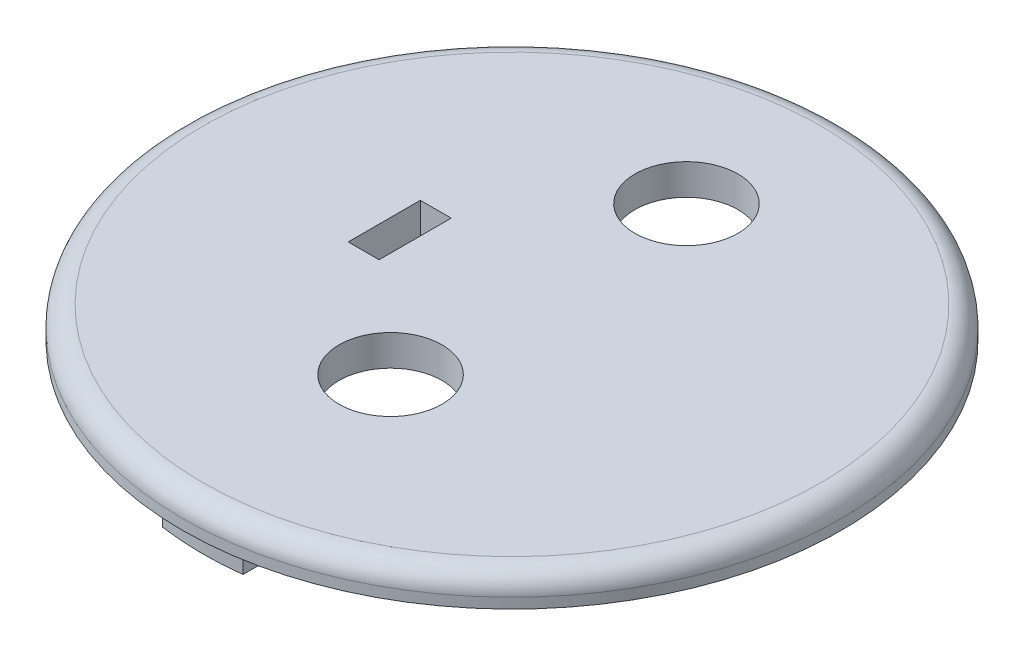
SolidWorks part; units mm, degrees
ref_plane "Plan de face" through (0, 0, 0) normal (0, 0, 1) x (1, 0, 0)
ref_plane "Plan de dessus" through (0, 0, 0) normal (0, 1, 0) x (1, 0, 0)
ref_plane "Plan de droite" through (0, 0, 0) normal (1, 0, 0) x (0, 0, -1)
sketch "Esquisse2" plane through (0, 0, 0) normal (0, 1, 0) x (1, 0, 0)
  line L0 (0, -11.7957) -> (0, 16.9396) construction
  circle A0 centre (0, 0) radius 32
  circle A1 centre (0, -11.7957) radius 5
  circle A2 centre (0, 16.9396) radius 5
  dimension "D1" = 10
  dimension "D2" = 10
extrude "Boss.-Extru.1" add sketch "Esquisse2" along normal blind 3
fillet "Congé1" radius 2 1 edges at (0, 3, 32)
sketch "Esquisse3" plane through (0, 0, 0) normal (0, -1, 0) x (1, 0, 0)
  line L0 (-4.2528, 29.697) -> (-4.2528, 28.0929)
  line L1 (-4.2528, 28.0929) -> (3.6548, 28.0929)
  line L2 (3.6548, 28.0929) -> (3.6548, 29.7765)
  line L3 (-30, 0) -> (-25.2439, 0) construction
  line L4 (-4.2528, -28.0929) -> (3.6548, -28.0929)
  line L5 (-4.2528, -29.697) -> (-4.2528, -28.0929)
  line L6 (3.6548, -28.0929) -> (3.6548, -29.7765)
  circle A0 centre (0, 0) radius 30
  spline S0 degree 2 poles (-4.2528, 29.697) (-0.3016, 30.2602) (3.6548, 29.7765) knots 0 0 0 1 1 1
  spline S1 degree 2 poles (-4.2528, -29.697) (-0.3016, -30.2602) (3.6548, -29.7765) knots 0 0 0 1 1 1
  dimension "D1" = 60
extrude "Boss.-Extru.2" add sketch "Esquisse3" along normal blind 3 contours L2 S0 L0 L1 | L4 L6 S1 L5
sketch "Esquisse4" plane through (0, 3, 0) normal (0, 1, 0) x (1, 0, 0)
  line L1 (-13.2037, 4.3) -> (-10.2037, 4.3)
  line L2 (-13.2037, 4.3) -> (-13.2037, -2.7)
  line L3 (-13.2037, -2.7) -> (-10.2037, -2.7)
  line L4 (-10.2037, 4.3) -> (-10.2037, -2.7)
  dimension "D1" = 3
  dimension "D2" = 7
extrude "Enlèv. mat.-Extru.1" cut sketch "Esquisse4" against normal blind 10
